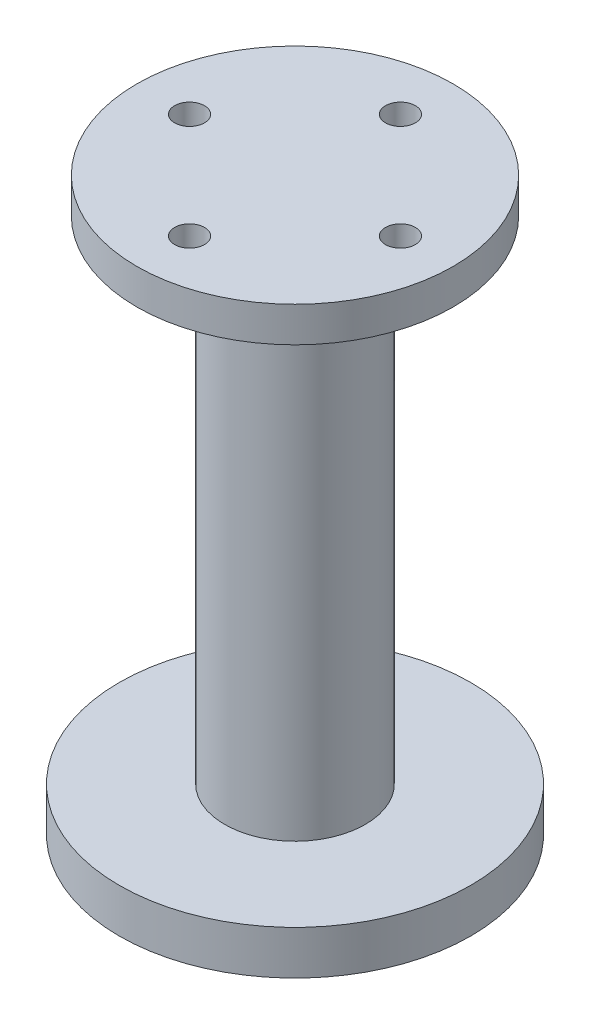
SolidWorks part; units mm, degrees
ref_plane "前视基准面" through (0, 0, 0) normal (0, 0, 1) x (1, 0, 0)
ref_plane "上视基准面" through (0, 0, 0) normal (0, 1, 0) x (1, 0, 0)
ref_plane "右视基准面" through (0, 0, 0) normal (1, 0, 0) x (0, 0, -1)
other "Configuration Table"
sketch "草图1" plane through (0, 0, 0) normal (0, 0, 1) x (1, 0, 0)
  line L0 (0, 0) -> (0, 78.3197) construction
  line L1 (0, 0) -> (-20, 0)
  line L2 (-20, 0) -> (-20, 5)
  line L3 (-20, 5) -> (-8, 5)
  line L4 (-8, 5) -> (-8, 61)
  line L5 (-8, 61) -> (-18, 61)
  line L6 (-18, 61) -> (-18, 65)
  line L7 (-18, 65) -> (0, 65)
  line L8 (0, 0) -> (0, 65)
  dimension "D1" = 5
  dimension "D2" = 4
  dimension "D3" = 20
  dimension "D4" = 36
  dimension "D5" = 65
  dimension "D6" = 16
revolve "旋转1" add sketch "草图1" angle 360 about L0
sketch "草图2" plane through (0, 65, 0) normal (0, 1, 0) x (1, 0, 0)
  line L0 (0, 0) -> (14.2261, 0) construction
  circle A0 centre (12, 0) radius 1.7
  circle A1 centre (0, -12) radius 1.7
  circle A2 centre (-12, 0) radius 1.7
  circle A3 centre (0, 12) radius 1.7
  point P14 (0, 0)
  dimension "D2" = 3.4
  dimension "D1" = 12
  dimension "D3" = 4
extrude "切除-拉伸1" cut sketch "草图2" against normal blind 10
